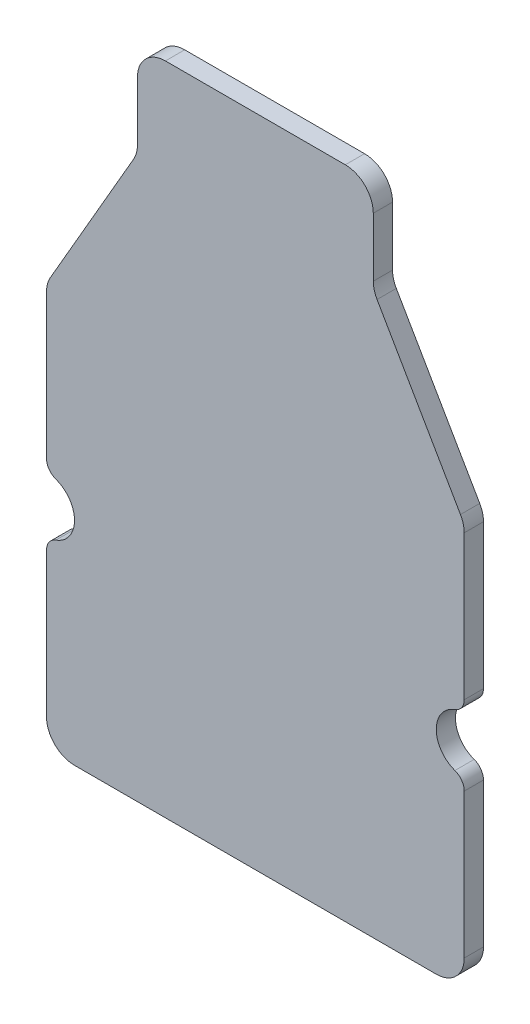
SolidWorks part; units mm, degrees
ref_plane "Front Plane" through (0, 0, 0) normal (0, 0, 1) x (1, 0, 0)
ref_plane "Top Plane" through (0, 0, 0) normal (0, 1, 0) x (1, 0, 0)
ref_plane "Right Plane" through (0, 0, 0) normal (1, 0, 0) x (0, 0, -1)
sketch "Sketch1" plane through (0, 0, 0) normal (0, 0, 1) x (1, 0, 0)
  line L0 (-74.65, 72.15) -> (-42.15, 128.4417)
  line L1 (74.65, -72.15) -> (-74.65, -72.15)
  line L2 (74.65, -72.15) -> (74.65, 72.15)
  line L3 (74.65, 72.15) -> (-74.65, 72.15) construction
  line L4 (-74.65, -72.15) -> (-74.65, 72.15)
  line L5 (74.65, -72.15) -> (-74.65, 72.15) construction
  line L6 (74.65, 72.15) -> (-74.65, -72.15) construction
  line L7 (-22.6885, 162.15) -> (22.6885, 162.15)
  line L8 (42.15, 128.4417) -> (74.65, 72.15)
  line L9 (-42.15, 128.4417) -> (-42.15, 162.15)
  line L10 (-42.15, 162.15) -> (-22.6885, 162.15)
  line L11 (22.6885, 162.15) -> (42.15, 162.15)
  line L12 (42.15, 162.15) -> (42.15, 128.4417)
  point P0 (0, 0)
  point P7 (0, 162.15)
  dimension "D1" = 149.3
  dimension "D2" = 144.3
  dimension "D3" = 150
  dimension "D4" = 90
  dimension "D5" = 84.3
extrude "Boss-Extrude1" add sketch "Sketch1" along normal blind 6.88
fillet "Fillet1" radius 10 8 edges at (74.65, -72.15, 3.44) (-74.65, -72.15, 3.44) (74.65, 72.15, 3.44) (-74.65, 72.15, 3.44) (42.15, 162.15, 3.44) (42.15, 128.4417, 3.44) (-42.15, 128.4417, 3.44) (-42.15, 162.15, 3.44)
sketch "Sketch2" plane through (0, 0, 6.88) normal (0, 0, 1) x (1, 0, 0)
  line L0 (-74.65, 69.4705) -> (-74.65, -62.15) construction
  line L1 (74.65, -62.15) -> (74.65, 69.4705) construction
  circle A0 centre (-74.65, 3.6603) radius 10
  circle A1 centre (74.65, 3.6603) radius 10
  dimension "D1" = 20
extrude "Cut-Extrude1" cut sketch "Sketch2" against normal through all
sketch "Sketch3" plane through (0, 0, 6.88) normal (0, 0, 1) x (1, 0, 0)
  line L0 (-40, 46.5) -> (62, -54.5) construction
  line L1 (62, -54.5) -> (-40, -54.5) construction
  line L2 (62, -54.5) -> (62, 46.5) construction
  line L3 (62, 46.5) -> (-40, 46.5) construction
  line L4 (-40, -54.5) -> (-40, 46.5) construction
  line L5 (11, -4) -> (11, 14.8824) construction
  line L6 (11, -4) -> (24.2716, -4) construction
  circle A0 centre (-40, 46.5) radius 1.775
  circle A1 centre (62, 46.5) radius 1.775
  circle A2 centre (-40, -54.5) radius 1.775
  circle A3 centre (62, -54.5) radius 1.775
  dimension "D3" = 3.55
  dimension "D1" = 102
  dimension "D2" = 101
  dimension "D4" = 4
  dimension "D5" = 11
extrude "Cut-Extrude2" [suppressed] cut sketch "Sketch3" against normal through all
sketch "Sketch4" plane through (0, 0, 6.88) normal (0, 0, 1) x (1, 0, 0)
  line L0 (22, -19.3293) -> (16, -19.3293) construction
  line L1 (-16, -51.3293) -> (-22, -51.3293) construction
  line L3 (-16, -19.3293) -> (16, -19.3293) construction
  line L4 (-16, -19.3293) -> (-16, -51.3293) construction
  line L5 (-16, -51.3293) -> (16, -51.3293) construction
  line L6 (16, -19.3293) -> (16, -51.3293) construction
  circle A0 centre (-22, -51.3293) radius 1.775
  circle A1 centre (22, -19.3293) radius 1.775
  circle A2 centre (0, -35.3293) radius 17.75 construction
  circle A3 centre (0, -35.3293) radius 7.5 construction
  arc A4 (0, -17.5793) -> (-14.665, -25.3293) centre (-7.3796, -21.3653) cw
  arc A5 (-14.665, -25.3293) -> (0, -17.5793) centre (0, -35.3293) cw
  circle A6 centre (-16, -19.3293) radius 1.775 construction
  circle A7 centre (-16, -51.3293) radius 1.775
  arc A8 (4.9788, -18.2919) -> (16.8813, -29.8443) centre (0, -35.3293) cw
  arc A9 (16.8813, -29.8443) -> (4.9788, -18.2919) centre (11.0002, -23.9958) cw
  circle A10 centre (16, -51.3293) radius 1.775 construction
  arc A11 (17.7421, -34.7996) -> (10.4332, -49.6894) centre (0, -35.3293) cw
  arc A12 (10.4332, -49.6894) -> (17.7421, -34.7996) centre (14.178, -42.2889) cw
  circle A13 centre (16, -19.3293) radius 1.775
  arc A14 (5.9864, -52.0394) -> (-10.4332, -49.6894) centre (0, -35.3293) cw
  arc A15 (-10.4332, -49.6894) -> (5.9864, -52.0394) centre (-2.2377, -50.9641) cw
  arc A16 (-14.0423, -46.1864) -> (-16.8813, -29.8443) centre (0, -35.3293) cw
  arc A17 (-16.8813, -29.8443) -> (-14.0423, -46.1864) centre (-15.561, -38.0326) cw
  point P11 (0, -19.3293)
  point P34 (0, -35.3293)
  dimension "D1" = 35.5
  dimension "D2" = 15
  dimension "D6" = 3.55
  dimension "D3" = 10
  dimension "D4" = 16
  dimension "D5" = 16
  dimension "D7" = 44
extrude "Cut-Extrude3" [suppressed] cut sketch "Sketch4" against normal through all
fillet "Fillet2" radius 5 4 edges at (74.65, 13.6603, 3.44) (74.65, -6.3397, 3.44) (-74.65, -6.3397, 3.44) (-74.65, 13.6603, 3.44)
sketch "Sketch5" plane through (0, 0, 6.88) normal (0, 0, 1) x (1, 0, 0)
  circle A0 centre (53.1812, -1.2926) radius 3.5065
extrude "Cut-Extrude4" [suppressed] cut sketch "Sketch5" against normal blind 10
sketch "Sketch6" plane through (0, 0, 6.88) normal (0, 0, 1) x (1, 0, 0)
  line L0 (71.2793, -36.4506) -> (70.5203, -34.0686) construction
  line L1 (70.5647, -36.6783) -> (69.8057, -34.2963)
  line L2 (71.9939, -36.2229) -> (71.2349, -33.8409)
  line L3 (73.6351, -35.6092) -> (67.8306, -17.3933) construction
  line L6 (66.287, -14.1958) -> (67.1796, -16.9971) construction
  line L7 (72.3591, -33.2518) -> (73.2517, -36.053) construction
  line L8 (66.287, -14.1958) -> (67.1796, -16.9971) construction
  line L9 (72.3591, -33.2518) -> (73.2517, -36.053) construction
  line L10 (82.7797, -33.0169) -> (81.8871, -30.2157) construction
  line L11 (76.7075, -13.961) -> (75.8149, -11.1598) construction
  line L12 (82.7797, -33.0169) -> (81.8871, -30.2157) construction
  line L13 (76.7075, -13.961) -> (75.8149, -11.1598) construction
  line L14 (82.3334, -31.6163) -> (72.8054, -34.6524) construction
  line L15 (72.8054, -34.6524) -> (70.8998, -35.2596) construction
  line L16 (76.2612, -12.5604) -> (66.7333, -15.5964) construction
  line L17 (64.8277, -16.2037) -> (66.7333, -15.5964) construction
  line L18 (70.8998, -35.2596) -> (72.8054, -34.6524) construction
  line L19 (84.6185, -32.2001) -> (83.8595, -29.8181) construction
  line L20 (83.9039, -32.4278) -> (83.1449, -30.0458)
  line L21 (85.3331, -31.9724) -> (84.5741, -29.5904)
  line L22 (78.5463, -13.1442) -> (77.7873, -10.7622) construction
  line L23 (77.8317, -13.3719) -> (77.0727, -10.9899)
  line L24 (79.2609, -12.9164) -> (78.5019, -10.5345)
  line L25 (65.2072, -17.3947) -> (64.4482, -15.0127) construction
  line L26 (64.4926, -17.6224) -> (63.7336, -15.2404)
  line L27 (65.9218, -17.167) -> (65.1627, -14.785)
  line L28 (84.239, -31.0091) -> (82.3334, -31.6163) construction
  line L29 (78.1668, -11.9532) -> (76.2612, -12.5604) construction
  arc A0 (70.5647, -36.6783) -> (71.9939, -36.2229) centre (71.2793, -36.4506) ccw
  arc A1 (71.2349, -33.8409) -> (69.8057, -34.2963) centre (70.5203, -34.0686) ccw
  arc A2 (83.9039, -32.4278) -> (85.3331, -31.9724) centre (84.6185, -32.2001) ccw
  arc A3 (84.5741, -29.5904) -> (83.1449, -30.0458) centre (83.8595, -29.8181) ccw
  arc A4 (77.8317, -13.3719) -> (79.2609, -12.9164) centre (78.5463, -13.1442) ccw
  arc A5 (78.5019, -10.5345) -> (77.0727, -10.9899) centre (77.7873, -10.7622) ccw
  arc A6 (64.4926, -17.6224) -> (65.9218, -17.167) centre (65.2072, -17.3947) ccw
  arc A7 (65.1627, -14.785) -> (63.7336, -15.2404) centre (64.4482, -15.0127) ccw
  point P2 (70.8998, -35.2596)
  point P26 (84.239, -31.0091)
  point P34 (78.1668, -11.9532)
  point P42 (64.8277, -16.2037)
  dimension "D1" = 0.75
  dimension "D2" = 2.5
  dimension "D3" = 2
extrude "Cut-Extrude5" [suppressed] cut sketch "Sketch6" against normal blind 10
